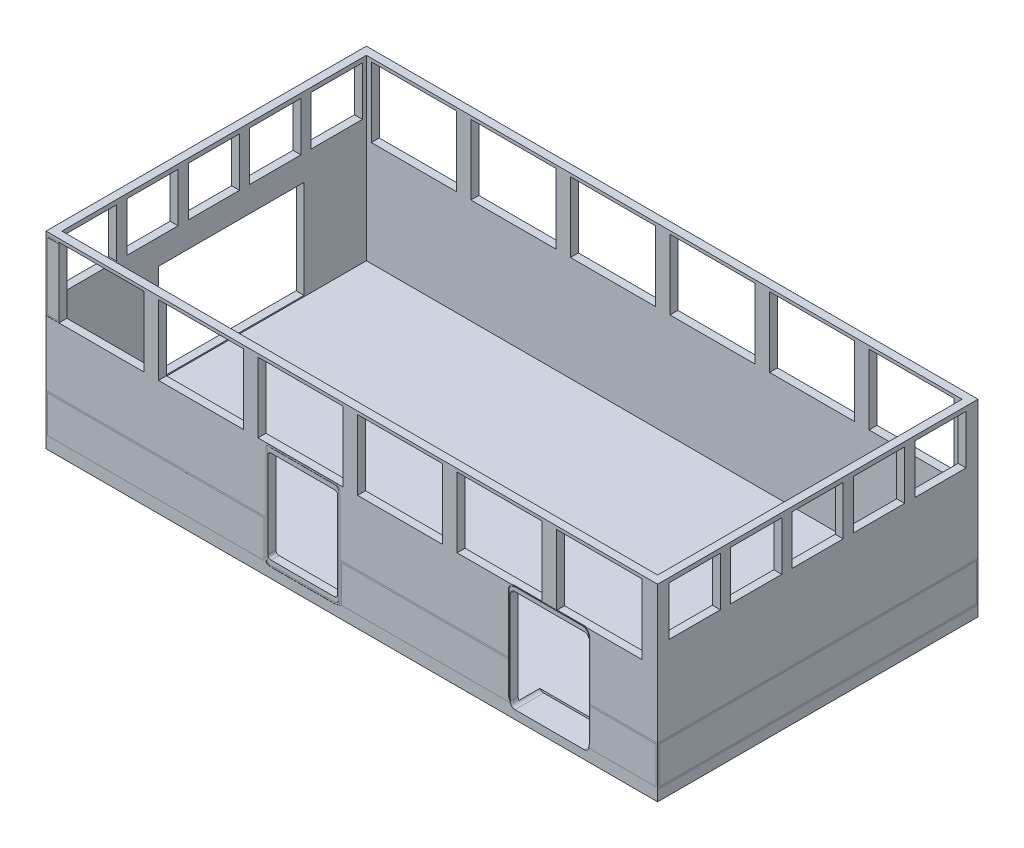
SolidWorks part; units mm, degrees
ref_plane "Alzado" through (0, 0, 0) normal (0, 0, 1) x (1, 0, 0)
ref_plane "Planta" through (0, 0, 0) normal (0, 1, 0) x (1, 0, 0)
ref_plane "Vista lateral" through (0, 0, 0) normal (1, 0, 0) x (0, 0, -1)
sketch "Croquis1" plane through (0, 0, 0) normal (0, 1, 0) x (1, 0, 0)
  line L0 (-5775, 3025) -> (-5775, -3025)
  line L1 (-5625, 2875) -> (5625, 2875)
  line L2 (-5625, 2875) -> (-5625, -2875)
  line L3 (-5625, -2875) -> (5625, -2875)
  line L4 (5625, 2875) -> (5625, -2875)
  line L5 (-5625, 2875) -> (5625, -2875) construction
  line L6 (-5625, -2875) -> (5625, 2875) construction
  line L7 (-5775, -3025) -> (5775, -3025)
  line L8 (5775, 3025) -> (5775, -3025)
  line L9 (-5775, 3025) -> (5775, 3025)
  point P0 (0, 0)
  dimension "D1" = 11250
  dimension "D2" = 5750
  dimension "D3" = 150
extrude "Saliente-Extruir1" add sketch "Croquis1" along normal blind 3360
sketch "Croquis2" plane through (0, 0, 0) normal (0, -1, 0) x (1, 0, 0)
  line L1 (-5775, 3025) -> (5775, 3025)
  line L2 (-5775, 3025) -> (-5775, -3025)
  line L3 (-5775, -3025) -> (5775, -3025)
  line L4 (5775, 3025) -> (5775, -3025)
  line L5 (-5775, 3025) -> (5775, -3025) construction
  line L6 (-5775, -3025) -> (5775, 3025) construction
  point P0 (0, 0)
extrude "Saliente-Extruir2" add sketch "Croquis2" along normal blind 200
sketch "Croquis3" plane through (0, 0, 3025) normal (0, 0, 1) x (1, 0, 0)
  line L0 (-5775, -200) -> (-5775, 1980) construction
  line L1 (-5775, 3360) -> (-5775, -200) construction
  line L2 (-5775, 1980) -> (5775, 1980) construction
  line L3 (-5775, 3300.8637) -> (-4353.7549, 3300.8637)
  line L4 (-5775, 3300.8637) -> (-5775, 1980)
  line L5 (-5775, 1980) -> (-4353.7549, 1980)
  line L6 (-4353.7549, 3300.8637) -> (-4353.7549, 1980)
  line L7 (-5775, 3300.8637) -> (-4353.7549, 1980) construction
  line L8 (-5775, 1980) -> (-4353.7549, 3300.8637) construction
  line L9 (5775, 3360) -> (5775, -200) construction
  line L10 (-4383.7549, 3270.8637) -> (-4383.7549, 2010)
  line L11 (-5745, 2010) -> (-4383.7549, 2010)
  line L12 (-5745, 3270.8637) -> (-5745, 2010)
  line L13 (-5745, 3270.8637) -> (-4383.7549, 3270.8637)
  point P5 (-5064.3774, 2640.4318)
  dimension "D1" = 2180
  dimension "D2" = 30
extrude "Cortar-Extruir1" cut sketch "Croquis3" against normal blind 3
sketch "Croquis5" plane through (-5775, 0, 0) normal (-1, 0, 0) x (0, 0, 1)
  line L1 (1840.1065, 3274.7201) -> (2807.6127, 3274.7201)
  line L2 (1840.1065, 3274.7201) -> (1840.1065, 2349.2794)
  line L3 (1840.1065, 2349.2794) -> (2807.6127, 2349.2794)
  line L4 (2807.6127, 3274.7201) -> (2807.6127, 2349.2794)
  point P7 (1442.8237, 1993.2506)
  point P9 (1718.584, 2353.9533)
  point P10 (2807.6127, 3274.7201)
  point P11 (1840.1065, 2349.2794)
extrude "Cortar-Extruir3" cut sketch "Croquis5" against normal blind 12126
pattern_linear "MatrizL3" count 5 spacing 1160 along (0, 0, -1) of "Cortar-Extruir3"
sketch "Croquis6" plane through (0, 0, 3025) normal (0, 0, 1) x (1, 0, 0)
  line L0 (0, 0) -> (-3847.4966, 0) construction
  line L1 (-1535, 1969.3183) -> (-315, 1969.3183)
  line L2 (-1625, 1879.3183) -> (-1625, 79.3183)
  line L3 (-1535, -10.6817) -> (-315, -10.6817)
  line L4 (-225, 1879.3183) -> (-225, 79.3183)
  line L5 (-1625, 1969.3183) -> (-225, -10.6817) construction
  line L6 (-1625, -10.6817) -> (-225, 1969.3183) construction
  line L7 (-1595, 1879.3183) -> (-1595, 79.3183)
  line L8 (-1535, 19.3183) -> (-315, 19.3183)
  line L9 (-255, 1879.3183) -> (-255, 79.3183)
  line L10 (-1535, 1939.3183) -> (-315, 1939.3183)
  line L11 (-225, 79.3183) -> (-225, -10.6817) construction
  line L12 (-225, -10.6817) -> (5775, -10.6817) construction
  line L13 (5775, 3360) -> (5775, -200) construction
  arc A0 (-1625, 79.3183) -> (-1535, -10.6817) centre (-1535, 79.3183) ccw
  arc A1 (-315, -10.6817) -> (-225, 79.3183) centre (-315, 79.3183) ccw
  arc A2 (-315, 1969.3183) -> (-225, 1879.3183) centre (-315, 1879.3183) cw
  arc A3 (-1535, 1969.3183) -> (-1625, 1879.3183) centre (-1535, 1879.3183) ccw
  arc A4 (-1625, 79.3183) -> (-1535, -10.6817) centre (-1535, 79.3183) ccw
  arc A5 (-1595, 79.3183) -> (-1535, 19.3183) centre (-1535, 79.3183) ccw
  arc A6 (-315, 19.3183) -> (-255, 79.3183) centre (-315, 79.3183) ccw
  arc A7 (-315, 1939.3183) -> (-255, 1879.3183) centre (-315, 1879.3183) cw
  arc A8 (-1535, 1939.3183) -> (-1595, 1879.3183) centre (-1535, 1879.3183) ccw
  point P0 (-925, 979.3183)
  dimension "D3" = 90
  dimension "D4" = 90
  dimension "D1" = 1980
  dimension "D2" = 1400
  dimension "D6" = 6000
  dimension "D5" = 30
extrude "Cortar-Extruir4" cut sketch "Croquis6" against normal blind 3 contours L1 A3 L2 A0 L3 A1 L4 A2 A8 L10 A7 L9 A6 L8 A5 L7
sketch "Croquis7" plane through (0, 0, 3025) normal (0, 0, 1) x (1, 0, 0)
  line L0 (-5775, -200) -> (-5775, 0)
  line L1 (-5775, 1980) -> (-5775, -200) construction
  line L2 (-5775, 0) -> (5775, 0)
  line L3 (5775, 3360) -> (5775, -200) construction
  line L4 (5775, 0) -> (5775, -200)
  line L5 (5775, -200) -> (-5775, -200)
extrude "Cortar-Extruir5" cut sketch "Croquis7" against normal blind 0.011
sketch "Croquis8" plane through (5775, 0, 0) normal (1, 0, 0) x (0, 0, -1)
  line L0 (-3024.989, -200) -> (-3025, 0)
  line L1 (-3025, 0) -> (3025, 0)
  line L2 (3025, 3360) -> (3025, -200) construction
  line L3 (3025, 0) -> (3025, -200)
  line L4 (3025, -200) -> (-3024.989, -200)
extrude "Cortar-Extruir6" cut sketch "Croquis8" against normal blind 0.011
sketch "Croquis9" plane through (0, 0, -3025) normal (0, 0, -1) x (-1, 0, 0)
  line L0 (-5774.989, -200) -> (-5774.989, 0)
  line L1 (-5774.989, 0) -> (5775, 0)
  line L2 (5775, 0) -> (5775, -200)
  line L3 (5775, -200) -> (-5774.989, -200)
extrude "Cortar-Extruir7" cut sketch "Croquis9" against normal blind 0.011
sketch "Croquis10" plane through (-5775, 0, 0) normal (-1, 0, 0) x (0, 0, 1)
  line L0 (-3024.989, -200) -> (-3024.989, 0)
  line L1 (-3024.989, 0) -> (3024.989, -10.6817)
  line L2 (3024.989, -10.6817) -> (3024.989, -200)
  line L3 (3024.989, -200) -> (-3024.989, -200)
extrude "Cortar-Extruir8" cut sketch "Croquis10" against normal blind 0.011
sketch "Croquis11" plane through (0, 0, -3025) normal (0, 0, -1) x (-1, 0, 0)
  line L0 (3924.134, 3300.8637) -> (5531.3417, 3300.8637)
  line L1 (4353.7549, 3300.8637) -> (5775, 3300.8637) construction
  line L2 (3924.134, 1980) -> (5531.3417, 1980)
  line L3 (5775, 1980) -> (4353.7549, 1980) construction
  line L4 (3924.134, 3300.8637) -> (3924.134, 1980)
  line L5 (5531.3417, 1980) -> (5531.3417, 3300.8637)
  point P0 (5531.3417, 3300.8637)
extrude "Cortar-Extruir9" cut sketch "Croquis11" against normal blind 6503.011
pattern_linear "MatrizL4" count 6 spacing 1880 along (1, 0, 0) of "Cortar-Extruir9"
sketch "Croquis12" plane through (-5775, 0, 0) normal (-1, 0, 0) x (0, 0, 1)
  line L0 (-1775, -2.207) -> (-1775, 1954.1197)
  line L1 (3024.989, -10.6817) -> (-3024.989, 0) construction
  line L2 (-1775, 1954.1197) -> (1125, 1954.1197)
  line L3 (1125, 1954.1197) -> (1125, -7.3271)
  line L4 (3024.989, -10.6817) -> (-3024.989, 0) construction
  line L5 (1125, -7.3271) -> (-1775, -2.207)
  line L6 (-1745, 27.7401) -> (-1745, 1924.1197)
  line L7 (-1745, 1924.1197) -> (1095, 1924.1197)
  line L8 (1095, 1924.1197) -> (1095, 22.7259)
  line L9 (1095, 22.7259) -> (-1745, 27.7401)
  line L10 (3025, 1980) -> (3025, 0) construction
  dimension "D2" = 2900
  dimension "D3" = 1900
  dimension "D1" = 30
extrude "Cortar-Extruir10" cut sketch "Croquis12" against normal blind 0.011
sketch "Croquis13" plane through (0, 0, 3025) normal (0, 0, 1) x (1, 0, 0)
  line L0 (-5775, 758.5264) -> (-1625, 758.5264)
  line L1 (-5775, 1980) -> (-5775, 0) construction
  line L2 (-1625, 1879.3183) -> (-1625, 79.3183) construction
  line L3 (-1625, 758.5264) -> (-1625, 0)
  line L4 (-1577.5278, 0) -> (-5775, 0) construction
  line L5 (-5775, 758.5264) -> (-5775, 0)
  line L6 (-5775, 0) -> (-1625, 0)
  line L7 (5775, 0) -> (5775, 758.5264)
  line L8 (5775, 3360) -> (5775, 0) construction
  line L9 (5775, 758.5264) -> (-225, 758.5264)
  line L10 (-225, 1879.3183) -> (-225, 79.3183) construction
  line L11 (-225, 758.5264) -> (-225, 0)
  line L12 (5774.989, 0) -> (-272.4722, 0) construction
  line L13 (-225, 0) -> (5775, 0)
  line L14 (-5745, 728.5264) -> (-5745, 30)
  line L15 (-5745, 30) -> (-1655, 30)
  line L16 (-1655, 728.5264) -> (-1655, 30)
  line L17 (-5745, 728.5264) -> (-1655, 728.5264)
  line L18 (5745, 728.5264) -> (-195, 728.5264)
  line L19 (-195, 728.5264) -> (-195, 30)
  line L20 (-195, 30) -> (5745, 30)
  line L21 (5745, 30) -> (5745, 728.5264)
  dimension "D1" = 30
extrude "Cortar-Extruir13" cut sketch "Croquis13" against normal blind 0.011
sketch "Croquis14" plane through (5775, 0, 0) normal (1, 0, 0) x (0, 0, -1)
  line L0 (-3024.989, 758.5264) -> (3025, 758.5264)
  line L1 (3025, 3360) -> (3025, 0) construction
  line L2 (3025, 758.5264) -> (3024.989, 0)
  line L3 (3024.989, 0) -> (-3024.989, 0)
  line L4 (-3024.989, 0) -> (-3024.989, 758.5264)
  line L5 (-2994.989, 30) -> (-2994.989, 728.5264)
  line L6 (-2994.989, 728.5264) -> (2994.9996, 728.5264)
  line L7 (2994.9996, 728.5264) -> (2994.9894, 30)
  line L8 (2994.9894, 30) -> (-2994.989, 30)
  dimension "D1" = 30
extrude "Cortar-Extruir14" cut sketch "Croquis14" against normal blind 0.0011
sketch "Croquis16" plane through (0, 0, -3025) normal (0, 0, -1) x (-1, 0, 0)
  line L0 (-5775, 0) -> (5774.989, 0)
  line L1 (-5774.9995, 758.5264) -> (-5775, 0)
  line L2 (-5774.9995, 758.5264) -> (5775, 758.5264)
  line L3 (5775, 758.5264) -> (5774.989, 0)
extrude "Saliente-Extruir3" add sketch "Croquis16" along normal blind 0.0011
sketch "Croquis17" plane through (-5775, 0, 0) normal (-1, 0, 0) x (0, 0, 1)
  line L0 (-1745, 1924.1197) -> (1095, 1924.1197)
  line L1 (1095, 1924.1197) -> (1095, -7.3271)
  line L2 (-1745, 1924.1197) -> (-1745, -7.3271)
  line L3 (-1745, -7.3271) -> (1095, -7.3271)
  line L4 (-1745, 1924.1197) -> (1095, 1924.1197)
  line M1 (-1745, 27.7401) -> (1095, 22.7259)
  line M2 (1095, 22.7259) -> (1095, 1924.1197)
  line M3 (1095, 1924.1197) -> (-1745, 1924.1197)
  line M4 (-1745, 1924.1197) -> (-1745, 27.7401)
extrude "Cortar-Extruir15" cut sketch "Croquis17" against normal blind 10 contours M4 M1 M2 M3
sketch "Croquis18" plane through (0, 0, 3025) normal (0, 0, 1) x (1, 0, 0)
  line L0 (-315, 1969.3183) -> (5775, 1969.3183) construction
  line L1 (5775, 3360) -> (5775, 758.5264) construction
  line L2 (5775, 1969.3183) -> (4475, 1969.3183) construction
  line L3 (4475, 1969.3183) -> (4475, 30) construction
  line L4 (-195, 30) -> (5745, 30) construction
  line L5 (2975, 1849.3183) -> (2975, 150)
  line L6 (-195, 30) -> (5745, 30) construction
  line L7 (3095, 30) -> (4355, 30)
  line L8 (3095, 1969.3183) -> (4355, 1969.3183)
  line L9 (4475, 1849.3183) -> (4475, 150)
  line L10 (2955, 1849.3183) -> (2955, 150)
  line L11 (3095, 10) -> (4355, 10)
  line L12 (4495, 1849.3183) -> (4495, 150)
  line L13 (3095, 1989.3183) -> (4355, 1989.3183)
  arc A0 (2975, 150) -> (3095, 30) centre (3095, 150) ccw
  arc A1 (4475, 150) -> (4355, 30) centre (4355, 150) cw
  arc A2 (4355, 1969.3183) -> (4475, 1849.3183) centre (4355, 1849.3183) cw
  arc A3 (2975, 1849.3183) -> (3095, 1969.3183) centre (3095, 1849.3183) cw
  arc A4 (2955, 150) -> (3095, 10) centre (3095, 150) ccw
  arc A5 (4495, 150) -> (4355, 10) centre (4355, 150) cw
  arc A6 (4355, 1989.3183) -> (4495, 1849.3183) centre (4355, 1849.3183) cw
  arc A7 (2955, 1849.3183) -> (3095, 1989.3183) centre (3095, 1849.3183) cw
  point P15 (2975, 30)
  point P24 (2975, 1969.3183)
  dimension "D3" = 120
  dimension "D1" = 1300
  dimension "D2" = 1500
  dimension "D4" = 20
extrude "Cortar-Extruir16" cut sketch "Croquis18" against normal blind 10
sketch "Croquis19" plane through (0, 0, 3025) normal (0, 0, 1) x (1, 0, 0)
  line L0 (-1595, 979.3183) -> (-255, 979.3183) construction
  line L1 (-1595, 1879.3183) -> (-1595, 79.3183) construction
  line L2 (-255, 1879.3183) -> (-255, 79.3183) construction
  line L3 (-255, 979.3183) -> (-925, 979.3183) construction
  line L4 (-925, 979.3183) -> (-925, 1939.3183) construction
  line L5 (-1535, 1939.3183) -> (-315, 1939.3183) construction
  line L7 (-325.9584, 104.3183) -> (-1524.0416, 104.3183)
  line L8 (-265.9584, 164.3183) -> (-265.9584, 1794.3183)
  line L9 (-325.9584, 1854.3183) -> (-1524.0416, 1854.3183)
  line L10 (-1584.0416, 164.3183) -> (-1584.0416, 1794.3183)
  line L11 (-265.9584, 104.3183) -> (-1584.0416, 1854.3183) construction
  line L12 (-265.9584, 1854.3183) -> (-1584.0416, 104.3183) construction
  arc A0 (-265.9584, 1794.3183) -> (-325.9584, 1854.3183) centre (-325.9584, 1794.3183) ccw
  arc A1 (-1524.0416, 104.3183) -> (-1584.0416, 164.3183) centre (-1524.0416, 164.3183) cw
  arc A2 (-325.9584, 104.3183) -> (-265.9584, 164.3183) centre (-325.9584, 164.3183) ccw
  arc A3 (-1524.0416, 1854.3183) -> (-1584.0416, 1794.3183) centre (-1524.0416, 1794.3183) ccw
  point P26 (-925, 104.3183)
  dimension "D1" = 60
  dimension "D2" = 1750
extrude "Cortar-Extruir17" cut sketch "Croquis19" against normal blind 625
sketch "Croquis20" plane through (0, 3360, 0) normal (0, 1, 0) x (1, 0, 0)
  line L1 (-5775, 3025) -> (5775, 3025)
  line L2 (-5775, 3025) -> (-5775, -3025)
  line L3 (-5775, -3025) -> (5775, -3025)
  line L4 (5775, 3025) -> (5775, -3025)
extrude "Saliente-Extruir4" [suppressed] add sketch "Croquis20" along normal blind 200
sketch "Croquis21" [suppressed] plane through (0, 3560, 0) normal (0, 1, 0) x (1, 0, 0)
  circle A0 centre (5300.4445, 2394.9026) radius 35.4333
extrude "Saliente-Extruir5" [suppressed] add sketch "Croquis21" along normal blind 3367
sketch "Croquis22" plane through (0, 0, 3025) normal (0, 0, 1) x (1, 0, 0)
  line L1 (3080.3364, 1891.432) -> (4388.8094, 1891.432)
  line L2 (2990.3364, 1801.432) -> (2990.3364, 51.432)
  line L3 (3080.3364, -38.568) -> (4388.8094, -38.568)
  line L4 (4478.8094, 1801.432) -> (4478.8094, 51.432)
  arc A0 (2990.3364, 51.432) -> (3080.3364, -38.568) centre (3080.3364, 51.432) ccw
  arc A1 (4388.8094, -38.568) -> (4478.8094, 51.432) centre (4388.8094, 51.432) ccw
  arc A2 (4388.8094, 1891.432) -> (4478.8094, 1801.432) centre (4388.8094, 1801.432) cw
  arc A3 (3080.3364, 1891.432) -> (2990.3364, 1801.432) centre (3080.3364, 1801.432) ccw
  point P12 (4388.8094, 1890.5757)
  dimension "D1" = 90
  dimension "D2" = 1750
extrude "Cortar-Extruir18" cut sketch "Croquis22" against normal blind 543
sketch "Croquis23" plane through (-5775, 0, 0) normal (-1, 0, 0) x (0, 0, 1)
  line L0 (-1745, 27.7401) -> (1095, 22.7259) construction
  line L1 (-1708.3765, 1891.282) -> (1053.6631, 1891.282)
  line L2 (-1708.3765, 1891.282) -> (-1708.3765, 22.7989)
  line L3 (-1708.3765, 22.7989) -> (1053.6631, 22.7989)
  line L4 (1053.6631, 1891.282) -> (1053.6631, 22.7989)
extrude "Cortar-Extruir19" cut sketch "Croquis23" against normal blind 10
sketch "Croquis25" plane through (-5765, 0, 0) normal (-1, 0, 0) x (0, 0, 1)
  line L1 (-1696.994, 1871.3919) -> (1053.6631, 1871.3919)
  line L2 (-1696.994, 1871.3919) -> (-1696.994, 22.7989)
  line L3 (-1696.994, 22.7989) -> (1053.6631, 22.7989)
  line L4 (1053.6631, 1871.3919) -> (1053.6631, 22.7989)
extrude "Cortar-Extruir20" cut sketch "Croquis25" against normal blind 679
